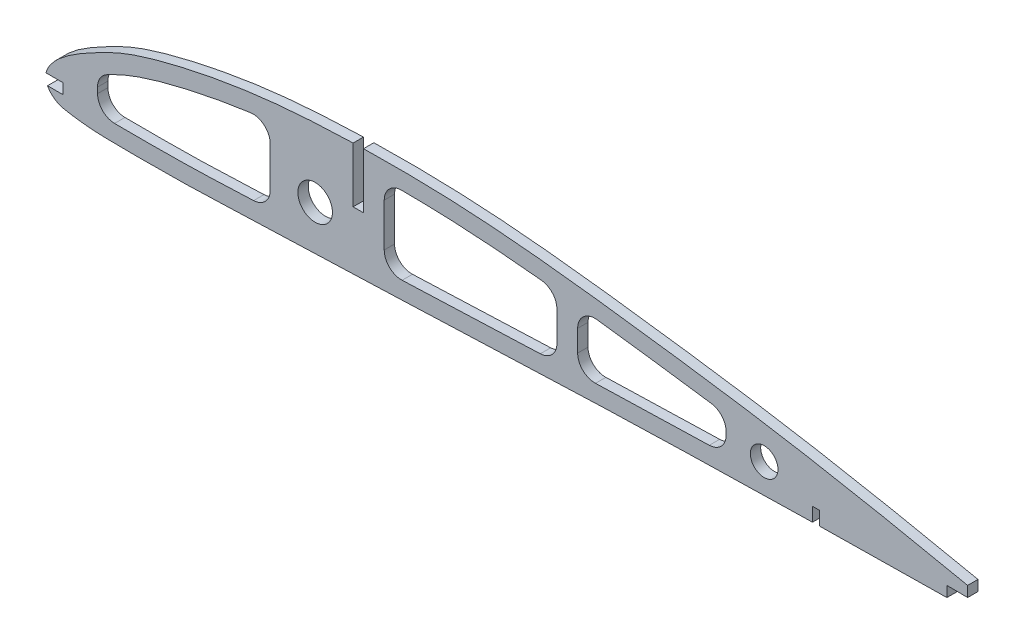
SolidWorks part; units mm, degrees
material "轻木"
ref_plane "前视基准面" through (0, 0, 0) normal (0, 0, 1) x (1, 0, 0)
ref_plane "上视基准面" through (0, 0, 0) normal (0, 1, 0) x (1, 0, 0)
ref_plane "右视基准面" through (0, 0, 0) normal (1, 0, 0) x (0, 0, -1)
other "Configuration Table"
curve "曲线1"
  spline degree 3 poles (300, 0.375, 0) (299.2857, 0.5355, 0) (297.8572, 0.8566, 0) (295.7147, 1.3378, 0) (293.5725, 1.8185, 0) (291.4302, 2.2982, 0) (289.2875, 2.7769, 0) (287.1442, 3.2543, 0) (285.001, 3.7299, 0) (282.8583, 4.2033, 0) (280.7163, 4.6744, 0) (278.5743, 5.1433, 0) (276.432, 5.6099, 0) (274.2889, 6.0741, 0) (272.145, 6.5358, 0) (269.2891, 7.1472, 0) (265.721, 7.9038, 0) (261.4399, 8.8, 0) (257.1573, 9.6847, 0) (252.8725, 10.5577, 0) (248.585, 11.4191, 0) (244.2942, 12.2686, 0) (240.0067, 13.1048, 0) (235.7231, 13.9276, 0) (231.4437, 14.735, 0) (227.1623, 15.5265, 0) (222.8779, 16.3002, 0) (218.5899, 17.0545, 0) (214.2976, 17.7876, 0) (210.0082, 18.4964, 0) (205.7223, 19.1793, 0) (201.441, 19.8388, 0) (197.1575, 20.4787, 0) (192.8717, 21.1016, 0) (188.5834, 21.71, 0) (184.2928, 22.3067, 0) (180.0042, 22.8936, 0) (175.7188, 23.4732, 0) (171.4371, 24.0431, 0) (167.1545, 24.6013, 0) (162.8704, 25.1452, 0) (158.5838, 25.6724, 0) (154.2938, 26.1804, 0) (150.0066, 26.6658, 0) (145.7226, 27.1265, 0) (141.4425, 27.5584, 0) (137.1601, 27.958, 0) (132.875, 28.3213, 0) (128.5869, 28.6439, 0) (124.2953, 28.9218, 0) (120.0053, 29.1506, 0) (115.7177, 29.3264, 0) (111.4337, 29.4514, 0) (107.1488, 29.5275, 0) (102.863, 29.5565, 0) (98.5762, 29.5401, 0) (94.2882, 29.4801, 0) (89.9957, 29.378, 0) (85.6999, 29.236, 0) (81.4026, 29.047, 0) (77.1093, 28.8043, 0) (72.8211, 28.5008, 0) (68.5389, 28.1296, 0) (64.264, 27.6835, 0) (60.7007, 27.2426, 0) (57.8461, 26.8442, 0) (55.696, 26.5216, 0) (53.5496, 26.1773, 0) (51.4067, 25.8115, 0) (49.2673, 25.4247, 0) (47.1314, 25.0171, 0) (44.9882, 24.5868, 0) (42.838, 24.1341, 0) (40.6818, 23.6568, 0) (38.5315, 23.1552, 0) (36.3875, 22.6273, 0) (34.2503, 22.0712, 0) (32.1202, 21.4847, 0) (30.3423, 20.9664, 0) (28.9132, 20.5311, 0) (27.8303, 20.1897, 0) (26.7518, 19.8362, 0) (25.6784, 19.4687, 0) (24.6112, 19.0858, 0) (23.551, 18.6856, 0) (22.4821, 18.2598, 0) (21.4059, 17.8057, 0) (20.3222, 17.3242, 0) (19.2465, 16.8243, 0) (18.1774, 16.3076, 0) (17.1139, 15.7762, 0) (16.0546, 15.2317, 0) (14.9819, 14.6674, 0) (13.8954, 14.0851, 0) (12.7977, 13.4827, 0) (11.7087, 12.8677, 0) (10.6313, 12.2387, 0) (9.5687, 11.5942, 0) (8.5237, 10.9329, 0) (7.6518, 10.3543, 0) (6.9458, 9.8665, 0) (6.3985, 9.4746, 0) (5.8573, 9.0705, 0) (5.3218, 8.651, 0) (4.7913, 8.2128, 0) (4.2653, 7.7527, 0) (3.6165, 7.1497, 0) (2.8604, 6.3846, 0) (2.0362, 5.4343, 0) (1.2959, 4.4252, 0) (0.6772, 3.3675, 0) (0.2189, 2.2697, 0) (-0.0383, 1.1392, 0) (-0.0456, 0.0749, 0) (0.1619, -0.885, 0) (0.4986, -1.7375, 0) (0.9635, -2.5517, 0) (1.5376, -3.3119, 0) (2.2026, -4.0019, 0) (2.94, -4.6051, 0) (3.6355, -5.044, 0) (4.2555, -5.3464, 0) (4.779, -5.5548, 0) (5.3118, -5.728, 0) (5.8521, -5.8723, 0) (6.398, -5.9938, 0) (6.9478, -6.0987, 0) (7.671, -6.2224, 0) (8.5669, -6.3647, 0) (9.636, -6.5177, 0) (10.7063, -6.6545, 0) (11.7778, -6.7754, 0) (12.8506, -6.8809, 0) (13.9246, -6.9713, 0) (14.9978, -7.047, 0) (16.0697, -7.1082, 0) (17.1403, -7.1566, 0) (18.2115, -7.1941, 0) (19.2831, -7.2222, 0) (20.3552, -7.2427, 0) (21.4275, -7.2573, 0) (22.4998, -7.2676, 0) (23.5718, -7.2752, 0) (24.6434, -7.2803, 0) (25.7147, -7.2832, 0) (26.7859, -7.2843, 0) (27.8572, -7.2839, 0) (28.9285, -7.2822, 0) (30.3573, -7.2788, 0) (32.1433, -7.2727, 0) (34.2864, -7.2613, 0) (36.4292, -7.2444, 0) (38.5718, -7.2208, 0) (40.7144, -7.1891, 0) (42.8572, -7.148, 0) (45.0005, -7.0962, 0) (47.1439, -7.0325, 0) (49.2871, -6.9587, 0) (51.4297, -6.8772, 0) (53.572, -6.7902, 0) (55.7143, -6.6999, 0) (57.857, -6.6086, 0) (60.7142, -6.4884, 0) (64.2858, -6.3465, 0) (68.5714, -6.1868, 0) (72.8565, -6.0353, 0) (77.1416, -5.8893, 0) (81.427, -5.7463, 0) (85.7132, -5.6038, 0) (90.0001, -5.4593, 0) (94.287, -5.3101, 0) (98.5731, -5.1566, 0) (102.8583, -4.9992, 0) (107.1431, -4.8383, 0) (111.4281, -4.6742, 0) (115.7138, -4.5074, 0) (120.0001, -4.3383, 0) (124.2865, -4.1673, 0) (128.5722, -3.9953, 0) (132.8572, -3.8233, 0) (137.142, -3.6525, 0) (141.4271, -3.4838, 0) (145.7131, -3.3181, 0) (149.9996, -3.1567, 0) (154.286, -3.0004, 0) (158.5714, -2.8495, 0) (162.8564, -2.7043, 0) (167.1412, -2.5651, 0) (171.4266, -2.4321, 0) (175.7128, -2.3056, 0) (179.9996, -2.1858, 0) (184.2862, -2.0731, 0) (188.5719, -1.9664, 0) (192.857, -1.8646, 0) (197.1419, -1.7668, 0) (201.4272, -1.6719, 0) (205.7132, -1.5788, 0) (209.9999, -1.4865, 0) (214.2864, -1.3941, 0) (218.5722, -1.3027, 0) (222.8572, -1.2136, 0) (227.142, -1.128, 0) (231.4272, -1.0471, 0) (235.7132, -0.9723, 0) (239.9998, -0.9046, 0) (244.2864, -0.8454, 0) (248.5722, -0.7928, 0) (252.8573, -0.7451, 0) (257.1422, -0.7003, 0) (261.4274, -0.6568, 0) (265.7134, -0.6127, 0) (269.2855, -0.574, 0) (272.1433, -0.5408, 0) (274.2862, -0.5157, 0) (276.4287, -0.4908, 0) (278.5712, -0.4671, 0) (280.7137, -0.4452, 0) (282.8567, -0.4258, 0) (285, -0.4096, 0) (287.1432, -0.3973, 0) (289.2862, -0.3884, 0) (291.4287, -0.3824, 0) (293.5711, -0.3786, 0) (295.7137, -0.3765, 0) (297.8567, -0.3754, 0) (299.2855, -0.3751, 0) (300, -0.375, 0) knots 0 0 0 0 0.003574 0.007146 0.010718 0.01429 0.017862 0.021434 0.025008 0.028577 0.032145 0.035713 0.03928 0.042847 0.046415 0.049985 0.057103 0.064219 0.071333 0.078448 0.085563 0.092679 0.099797 0.106885 0.11397 0.121053 0.128137 0.13522 0.142305 0.149391 0.15644 0.163488 0.170534 0.17758 0.184627 0.191675 0.198725 0.205755 0.212782 0.219809 0.226834 0.233861 0.240889 0.24792 0.254921 0.26192 0.268917 0.275914 0.28291 0.289907 0.296905 0.303879 0.310852 0.317824 0.324796 0.331771 0.338748 0.345728 0.352728 0.359727 0.366723 0.373717 0.380709 0.387701 0.394695 0.398233 0.40177 0.405307 0.408843 0.41238 0.415918 0.419457 0.42305 0.426643 0.430235 0.433828 0.43742 0.441014 0.444611 0.446459 0.448306 0.450153 0.451999 0.453844 0.455687 0.45753 0.459459 0.461388 0.463318 0.465249 0.467183 0.469121 0.471062 0.4731 0.475138 0.477173 0.479204 0.481227 0.483239 0.48524 0.486334 0.487428 0.488525 0.48963 0.490748 0.491883 0.493041 0.495071 0.497131 0.499176 0.501171 0.503098 0.50496 0.506796 0.508242 0.509728 0.511253 0.512804 0.514366 0.515919 0.517444 0.518368 0.519283 0.520192 0.521101 0.522011 0.522922 0.523833 0.525592 0.527349 0.529104 0.530859 0.532612 0.534366 0.53612 0.537863 0.539607 0.54135 0.543094 0.544839 0.546584 0.548329 0.550073 0.551817 0.55356 0.555302 0.557045 0.558788 0.560532 0.564019 0.567506 0.570992 0.574478 0.577965 0.581452 0.584939 0.588429 0.591918 0.595406 0.598895 0.602383 0.605872 0.609363 0.616342 0.623319 0.630295 0.637271 0.644247 0.651224 0.658203 0.665183 0.672161 0.679137 0.686114 0.69309 0.700068 0.707048 0.714028 0.721006 0.727983 0.73496 0.741937 0.748915 0.755896 0.762874 0.769851 0.776826 0.783801 0.790777 0.797753 0.804732 0.811709 0.818683 0.825657 0.83263 0.839604 0.846578 0.853555 0.860532 0.867506 0.874479 0.881452 0.888424 0.895399 0.902375 0.90935 0.916324 0.923296 0.930267 0.937239 0.944213 0.951188 0.954676 0.958163 0.961649 0.965135 0.96862 0.972107 0.975595 0.979082 0.982569 0.986054 0.98954 0.993026 0.996512 1 1 1 1
curve "曲线2"
  spline degree 3 poles (299.6892, 0.0825, 0) (300.1498, -0.0478, 0) (299.7114, 0.1074, 0) (299.5104, 0.1872, 0) (299.2477, 0.2871, 0) (298.8504, 0.4413, 0) (298.294, 0.6613, 0) (297.5919, 0.9463, 0) (296.8903, 1.2362, 0) (296.0644, 1.581, 0) (295.1136, 1.9799, 0) (294.0373, 2.431, 0) (292.9597, 2.8788, 0) (291.7683, 3.3665, 0) (290.4608, 3.8877, 0) (289.0365, 4.4399, 0) (287.6073, 4.9796, 0) (286.0635, 5.5484, 0) (284.4048, 6.1444, 0) (282.6311, 6.7664, 0) (280.8534, 7.377, 0) (278.9651, 8.0149, 0) (276.9667, 8.6805, 0) (274.8582, 9.373, 0) (272.7471, 10.0574, 0) (270.5382, 10.7652, 0) (268.2318, 11.4959, 0) (265.8278, 12.2485, 0) (263.4214, 12.9932, 0) (260.9293, 13.7558, 0) (258.3517, 14.5354, 0) (255.6885, 15.3308, 0) (253.0225, 16.1168, 0) (250.2835, 16.9138, 0) (247.4714, 17.7205, 0) (244.5864, 18.536, 0) (241.6982, 19.3402, 0) (238.749, 20.1489, 0) (235.7391, 20.9612, 0) (232.6684, 21.7757, 0) (229.594, 22.5763, 0) (226.4711, 23.374, 0) (223.2997, 24.1675, 0) (220.08, 24.9553, 0) (216.8561, 25.726, 0) (213.5945, 26.4871, 0) (210.2953, 27.2373, 0) (206.9588, 27.975, 0) (203.6178, 28.6919, 0) (200.2497, 29.3918, 0) (196.8549, 30.0732, 0) (193.4336, 30.7349, 0) (190.0077, 31.3718, 0) (186.5618, 31.9862, 0) (183.0963, 32.577, 0) (179.6117, 33.1436, 0) (176.1229, 33.6833, 0) (172.6234, 34.197, 0) (169.1136, 34.6844, 0) (165.5943, 35.1447, 0) (162.0713, 35.5767, 0) (158.5465, 35.9798, 0) (155.0205, 36.3535, 0) (151.4939, 36.6979, 0) (147.9646, 37.0129, 0) (144.4431, 37.2978, 0) (140.9302, 37.5529, 0) (137.4264, 37.7777, 0) (133.9208, 37.9727, 0) (130.4332, 38.1365, 0) (126.9642, 38.269, 0) (123.5147, 38.3706, 0) (120.0643, 38.4412, 0) (116.6408, 38.4803, 0) (113.2449, 38.4881, 0) (109.8772, 38.4649, 0) (106.5099, 38.4098, 0) (103.1795, 38.3231, 0) (99.8867, 38.2053, 0) (96.6323, 38.0567, 0) (93.3796, 37.8749, 0) (90.1728, 37.6618, 0) (87.0127, 37.4182, 0) (83.9, 37.1447, 0) (80.7905, 36.8368, 0) (77.7347, 36.4989, 0) (74.7332, 36.1323, 0) (71.7867, 35.7377, 0) (68.8452, 35.3075, 0) (65.9638, 34.8492, 0) (63.1431, 34.3642, 0) (60.3838, 33.8535, 0) (57.6314, 33.3063, 0) (54.9457, 32.7337, 0) (52.327, 32.1376, 0) (49.7758, 31.5197, 0) (47.2337, 30.8655, 0) (44.763, 30.1905, 0) (42.364, 29.4973, 0) (40.0371, 28.7872, 0) (37.7217, 28.0406, 0) (35.4836, 27.2778, 0) (33.323, 26.5013, 0) (31.2399, 25.7132, 0) (29.1709, 24.8888, 0) (27.1829, 24.0541, 0) (25.2756, 23.212, 0) (23.4491, 22.3647, 0) (21.6401, 21.481, 0) (19.9159, 20.5922, 0) (18.2759, 19.7016, 0) (16.7198, 18.8121, 0) (15.1846, 17.8866, 0) (13.7354, 16.9627, 0) (12.3708, 16.045, 0) (11.0909, 15.1361, 0) (9.8373, 14.192, 0) (8.6721, 13.2572, 0) (7.5935, 12.336, 0) (6.5993, 11.4319, 0) (5.6356, 10.4933, 0) (4.7571, 9.5716, 0) (3.961, 8.6731, 0) (3.2484, 7.802, 0) (2.5791, 6.9017, 0) (2.0018, 6.0303, 0) (1.5119, 5.1928, 0) (1.098, 4.3932, 0) (0.723, 3.565, 0) (0.4148, 2.7772, 0) (0.1635, 2.0409, 0) (-0.0076, 1.362, 0) (-0.0857, 0.6761, 0) (-0.0312, 0.0318, 0) (0.1575, -0.5446, 0) (0.4284, -1.0495, 0) (0.7766, -1.5095, 0) (1.2499, -1.9767, 0) (1.8739, -2.4002, 0) (2.6419, -2.7457, 0) (3.4475, -3.0028, 0) (4.3968, -3.243, 0) (5.4726, -3.4987, 0) (6.6732, -3.7581, 0) (7.8724, -3.9885, 0) (9.2039, -4.2095, 0) (10.6736, -4.4054, 0) (12.2821, -4.571, 0) (13.8972, -4.6995, 0) (15.6445, -4.8094, 0) (17.5211, -4.9053, 0) (19.5261, -4.9826, 0) (21.5305, -5.0368, 0) (23.661, -5.0721, 0) (25.9181, -5.0854, 0) (28.3014, -5.0749, 0) (30.6852, -5.0437, 0) (33.1885, -4.993, 0) (35.8107, -4.9237, 0) (38.5514, -4.8343, 0) (41.2914, -4.7299, 0) (44.1429, -4.6075, 0) (47.1057, -4.467, 0) (50.1792, -4.3077, 0) (53.2522, -4.1367, 0) (56.4269, -3.9498, 0) (59.7026, -3.7473, 0) (63.0791, -3.5293, 0) (66.4551, -3.3033, 0) (69.9209, -3.0645, 0) (73.4761, -2.8134, 0) (77.1202, -2.5502, 0) (80.764, -2.2824, 0) (84.4846, -2.0051, 0) (88.2815, -1.7191, 0) (92.1543, -1.4245, 0) (96.027, -1.128, 0) (99.9621, -0.8252, 0) (103.9592, -0.5167, 0) (108.0179, -0.2032, 0) (112.0767, 0.1098, 0) (116.1823, 0.4251, 0) (120.3344, 0.742, 0) (124.5324, 1.0596, 0) (128.7308, 1.3739, 0) (132.9595, 1.6861, 0) (137.2181, 1.9957, 0) (141.506, 2.3018, 0) (145.7945, 2.6016, 0) (150.096, 2.8954, 0) (154.41, 3.1825, 0) (158.7362, 3.4618, 0) (163.063, 3.7316, 0) (167.3848, 3.9907, 0) (171.7011, 4.2382, 0) (176.0115, 4.4733, 0) (180.3226, 4.6957, 0) (184.6083, 4.9033, 0) (188.8679, 5.0957, 0) (193.1011, 5.2721, 0) (197.335, 5.4325, 0) (201.5222, 5.5742, 0) (205.6623, 5.6969, 0) (209.7546, 5.8004, 0) (213.8473, 5.8854, 0) (217.8716, 5.9498, 0) (221.8268, 5.9942, 0) (225.7124, 6.0188, 0) (229.598, 6.0233, 0) (233.3935, 6.0071, 0) (237.0983, 5.971, 0) (240.7119, 5.9157, 0) (244.325, 5.8393, 0) (247.8275, 5.7436, 0) (251.2186, 5.6301, 0) (254.498, 5.5, 0) (257.7765, 5.3484, 0) (260.9253, 5.1809, 0) (263.9441, 4.9996, 0) (266.8324, 4.8058, 0) (269.7191, 4.5899, 0) (272.4587, 4.362, 0) (275.0509, 4.1249, 0) (277.4951, 3.8799, 0) (279.9368, 3.6105, 0) (282.2113, 3.3338, 0) (284.3185, 3.0537, 0) (286.2585, 2.7745, 0) (288.195, 2.4723, 0) (289.9467, 2.1761, 0) (291.5141, 1.8919, 0) (292.8979, 1.6262, 0) (294.2788, 1.3456, 0) (295.4709, 1.0894, 0) (296.4751, 0.8638, 0) (297.2928, 0.6738, 0) (298.1076, 0.4784, 0) (298.7442, 0.3204, 0) (299.1896, 0.208, 0) (299.4728, 0.1348, 0) (299.6892, 0.0825, 0) (300.1498, -0.0478, 0) (299.7114, 0.1074, 0) knots -0.001345 -0.000897 -0.000449 0 0.000432 0.000863 0.001295 0.001726 0.002951 0.004176 0.0054 0.006625 0.008509 0.010392 0.012274 0.014158 0.016623 0.019088 0.021553 0.024019 0.027053 0.030085 0.033118 0.036152 0.039734 0.043315 0.046896 0.050478 0.054544 0.058608 0.062672 0.066738 0.071224 0.075709 0.080193 0.084679 0.089518 0.094356 0.099193 0.104032 0.10916 0.114286 0.119411 0.124539 0.129889 0.135237 0.140585 0.145936 0.151451 0.156964 0.162478 0.167993 0.173617 0.17924 0.184862 0.190486 0.196184 0.20188 0.207576 0.213274 0.219003 0.22473 0.230457 0.236185 0.241905 0.247622 0.253339 0.259058 0.264725 0.270389 0.276054 0.281721 0.287291 0.29286 0.298428 0.303998 0.309434 0.314867 0.320301 0.325737 0.330995 0.336251 0.341507 0.346766 0.351809 0.356851 0.361892 0.366936 0.371734 0.37653 0.381327 0.386125 0.390654 0.395182 0.399709 0.404238 0.408475 0.41271 0.416945 0.421182 0.425109 0.429034 0.432959 0.436885 0.44048 0.444073 0.447666 0.451261 0.454511 0.457759 0.461007 0.464256 0.467149 0.470041 0.472933 0.475826 0.47836 0.480893 0.483425 0.485956 0.488123 0.490291 0.49246 0.494634 0.496453 0.49827 0.500081 0.501882 0.503328 0.504776 0.506239 0.507727 0.50887 0.510003 0.51111 0.512198 0.513104 0.514027 0.514959 0.515886 0.517235 0.518584 0.51995 0.521324 0.523324 0.525303 0.52727 0.529235 0.531836 0.534446 0.537062 0.539679 0.542921 0.546158 0.549393 0.552628 0.556473 0.560319 0.564166 0.568014 0.57244 0.576864 0.581288 0.585714 0.590681 0.595647 0.600613 0.605581 0.611042 0.616501 0.62196 0.627422 0.633319 0.639214 0.645109 0.651006 0.657275 0.663542 0.669809 0.676078 0.682648 0.689216 0.695784 0.702355 0.70915 0.715943 0.722736 0.729531 0.73647 0.743406 0.750342 0.757281 0.764278 0.771273 0.778268 0.785265 0.792232 0.799197 0.806162 0.81313 0.819969 0.826805 0.833641 0.840479 0.847087 0.853692 0.860297 0.866904 0.873175 0.879445 0.885714 0.891986 0.897819 0.90365 0.909481 0.915314 0.920611 0.925907 0.931202 0.936499 0.941172 0.945842 0.950513 0.955185 0.95915 0.963114 0.967077 0.971042 0.974206 0.977368 0.98053 0.983693 0.985968 0.988241 0.990515 0.992789 0.994144 0.995498 0.996852 0.998206 0.998655 0.999103 0.999551 1 1.000432 1.000863 1.001295 periodic
sketch "草图1" plane through (0, 0, 0) normal (0, 0, 1) x (1, 0, 0)
  line L1 (290, 2.6177) -> (290, -0.3866)
  line L2 (289, 1.8162) -> (289, 0.6101)
  line L3 (0, 0) -> (0, 30) construction
  line L4 (-6, -1.5) -> (6, -1.5)
  line L5 (-6, -1.5) -> (-6, 1.5)
  line L6 (-6, 1.5) -> (6, 1.5)
  line L7 (6, -1.5) -> (6, 1.5)
  line L8 (-6, -1.5) -> (6, 1.5) construction
  line L9 (-6, 1.5) -> (6, -1.5) construction
  line L10 (-1000, 0) -> (49000, 0) construction
  line L11 (90, 29.3715) -> (93, 29.3715)
  line L12 (90, 29.3715) -> (90, 12.3715)
  line L13 (90, 12.3715) -> (93, 12.3715)
  line L14 (93, 29.3715) -> (93, 12.3715)
  line L16 (223, -1.2113) -> (225, -1.2113)
  line L17 (223, -1.2113) -> (223, 3.7887)
  line L18 (223, 3.7887) -> (225, 3.7887)
  line L19 (225, -1.2113) -> (225, 3.7887)
  circle A0 centre (79, 8) radius 5
  circle A1 centre (209, 8) radius 4
  spline S0 degree 3 poles (1772.1833, 2527.0993) (871.6721, -135.2205) (584.8189, -63.6019) (295.7147, 1.3378) (293.5725, 1.8185) (291.4302, 2.2982) (289.2875, 2.7769) (287.1442, 3.2543) (285.001, 3.7299) (282.8583, 4.2033) (280.7163, 4.6744) (278.5743, 5.1433) (276.432, 5.6099) (274.2889, 6.0741) (272.145, 6.5358) (269.2891, 7.1472) (265.721, 7.9038) (261.4399, 8.8) (257.1573, 9.6847) (252.8725, 10.5577) (248.585, 11.4191) (244.2942, 12.2686) (240.0067, 13.1048) (234.2978, 14.2013) (228.5907, 15.2685) (222.8779, 16.3002) (218.5899, 17.0545) (214.2976, 17.7876) (210.0082, 18.4964) (205.7223, 19.1793) (201.441, 19.8388) (197.1575, 20.4787) (192.8717, 21.1016) (188.5834, 21.71) (184.2928, 22.3067) (180.0042, 22.8936) (175.7188, 23.4732) (171.4371, 24.0431) (167.1545, 24.6013) (162.8704, 25.1452) (158.5838, 25.6724) (154.2938, 26.1804) (150.0066, 26.6658) (145.7226, 27.1265) (141.4425, 27.5584) (137.1601, 27.958) (132.875, 28.3213) (128.5869, 28.6439) (124.2953, 28.9218) (120.0053, 29.1506) (115.7177, 29.3264) (111.4337, 29.4514) (107.1488, 29.5275) (102.863, 29.5565) (98.5762, 29.5401) (94.2882, 29.4801) (89.9957, 29.378) (85.6999, 29.236) (81.4026, 29.047) (77.1093, 28.8043) (72.8211, 28.5008) (68.5389, 28.1296) (64.264, 27.6835) (60.7007, 27.2426) (57.1284, 26.744) (53.5478, 26.188) (49.9791, 25.5605) (47.1314, 25.0171) (44.9882, 24.5868) (42.838, 24.1341) (40.6818, 23.6568) (38.5315, 23.1552) (36.3875, 22.6273) (34.2503, 22.0712) (32.1202, 21.4847) (30.3423, 20.9664) (28.9132, 20.5311) (27.8303, 20.1897) (26.7518, 19.8362) (25.6784, 19.4687) (24.6112, 19.0858) (23.551, 18.6856) (22.4821, 18.2598) (21.4059, 17.8057) (20.3222, 17.3242) (19.2465, 16.8243) (18.1774, 16.3076) (17.1139, 15.7762) (16.0546, 15.2317) (14.9819, 14.6674) (13.8954, 14.0851) (12.7977, 13.4827) (11.7087, 12.8677) (10.6313, 12.2387) (9.5687, 11.5942) (8.5237, 10.9329) (7.6518, 10.3543) (6.9458, 9.8665) (6.3985, 9.4746) (5.8573, 9.0705) (5.3218, 8.651) (4.7913, 8.2128) (4.2653, 7.7527) (3.6165, 7.1497) (2.8604, 6.3846) (2.0362, 5.4343) (1.2959, 4.4252) (0.6772, 3.3675) (0.2189, 2.2697) (-0.0383, 1.1392) (-0.0456, 0.0749) (0.1619, -0.885) (0.4986, -1.7375) (0.9635, -2.5517) (1.5376, -3.3119) (2.2026, -4.0019) (2.94, -4.6051) (3.6355, -5.044) (4.2555, -5.3464) (4.779, -5.5548) (5.3118, -5.728) (5.8521, -5.8723) (6.398, -5.9938) (6.9478, -6.0987) (7.671, -6.2224) (8.5669, -6.3647) (9.9918, -6.5686) (11.4199, -6.7402) (12.8506, -6.8809) (13.9246, -6.9713) (14.9978, -7.047) (16.0697, -7.1082) (17.1403, -7.1566) (18.2115, -7.1941) (19.2831, -7.2222) (20.3552, -7.2427) (21.4275, -7.2573) (22.4998, -7.2676) (23.5718, -7.2752) (24.6434, -7.2803) (25.7147, -7.2832) (27.143, -7.2847) (28.5715, -7.283) (30.3573, -7.2788) (32.1433, -7.2727) (34.2864, -7.2613) (36.4292, -7.2444) (38.5718, -7.2208) (40.7144, -7.1891) (42.8572, -7.148) (45.0005, -7.0962) (47.1439, -7.0325) (49.2871, -6.9587) (51.4297, -6.8772) (54.2862, -6.7612) (57.1429, -6.6386) (60.7142, -6.4884) (64.2858, -6.3465) (69.9995, -6.1336) (75.7132, -5.9369) (81.427, -5.7463) (85.7132, -5.6038) (90.0001, -5.4593) (94.287, -5.3101) (98.5731, -5.1566) (102.8583, -4.9992) (108.5717, -4.7846) (114.2856, -4.5638) (120.0001, -4.3383) (124.2865, -4.1673) (128.5722, -3.9953) (132.8572, -3.8233) (137.142, -3.6525) (141.4271, -3.4838) (145.7131, -3.3181) (149.9996, -3.1567) (154.286, -3.0004) (158.5714, -2.8495) (164.2846, -2.656) (171.4272, -2.4288) (179.9991, -2.1823) (187.1429, -2.0003) (192.857, -1.8646) (197.1419, -1.7668) (201.4272, -1.6719) (205.7132, -1.5788) (209.9999, -1.4865) (214.2864, -1.3941) (218.5722, -1.3027) (222.8572, -1.2136) (227.142, -1.128) (231.4272, -1.0471) (235.7132, -0.9723) (239.9998, -0.9046) (244.2864, -0.8454) (248.5722, -0.7928) (252.8573, -0.7451) (258.5708, -0.6854) (264.285, -0.6282) (269.2855, -0.574) (272.1433, -0.5408) (274.2862, -0.5157) (276.4287, -0.4908) (278.5712, -0.4671) (280.7137, -0.4452) (282.8567, -0.4258) (285, -0.4096) (287.1432, -0.3973) (289.2862, -0.3884) (291.4287, -0.3824) (293.5711, -0.3786) (295.7137, -0.3765) (521.6922, -0.2702) (746.959, -9.4705) (970.7683, 2878.2814) knots -1.435568 -1.435568 -1.435568 -1.435568 0.003574 0.007146 0.010718 0.01429 0.017862 0.021434 0.025008 0.028577 0.032145 0.035713 0.03928 0.042847 0.046415 0.049985 0.057103 0.064219 0.071333 0.078448 0.085563 0.092679 0.099797 0.106885 0.121053 0.128137 0.13522 0.142305 0.149391 0.15644 0.163488 0.170534 0.17758 0.184627 0.191675 0.198725 0.205755 0.212782 0.219809 0.226834 0.233861 0.240889 0.24792 0.254921 0.26192 0.268917 0.275914 0.28291 0.289907 0.296905 0.303879 0.310852 0.317824 0.324796 0.331771 0.338748 0.345728 0.352728 0.359727 0.366723 0.373717 0.380709 0.387701 0.394695 0.398233 0.405307 0.41238 0.415918 0.419457 0.42305 0.426643 0.430235 0.433828 0.43742 0.441014 0.444611 0.446459 0.448306 0.450153 0.451999 0.453844 0.455687 0.45753 0.459459 0.461388 0.463318 0.465249 0.467183 0.469121 0.471062 0.4731 0.475138 0.477173 0.479204 0.481227 0.483239 0.48524 0.486334 0.487428 0.488525 0.48963 0.490748 0.491883 0.493041 0.495071 0.497131 0.499176 0.501171 0.503098 0.50496 0.506796 0.508242 0.509728 0.511253 0.512804 0.514366 0.515919 0.517444 0.518368 0.519283 0.520192 0.521101 0.522011 0.522922 0.523833 0.525592 0.527349 0.530859 0.532612 0.534366 0.53612 0.537863 0.539607 0.54135 0.543094 0.544839 0.546584 0.548329 0.550073 0.551817 0.55356 0.555302 0.558788 0.560532 0.564019 0.567506 0.570992 0.574478 0.577965 0.581452 0.584939 0.588429 0.591918 0.595406 0.598895 0.605872 0.609363 0.616342 0.623319 0.637271 0.644247 0.651224 0.658203 0.665183 0.672161 0.679137 0.686114 0.700068 0.707048 0.714028 0.721006 0.727983 0.73496 0.741937 0.748915 0.755896 0.762874 0.769851 0.776826 0.790777 0.804732 0.818683 0.825657 0.83263 0.839604 0.846578 0.853555 0.860532 0.867506 0.874479 0.881452 0.888424 0.895399 0.902375 0.90935 0.916324 0.923296 0.930267 0.944213 0.951188 0.954676 0.958163 0.961649 0.965135 0.96862 0.972107 0.975595 0.979082 0.982569 0.986054 0.98954 0.993026 0.996512 2.092547 2.092547 2.092547 2.092547 only from (300, 0.375) to (300, -0.375) construction
  spline S1 degree 3 poles (290, 2.6177) (289.0482, 2.8302) (287.3817, 3.2016) (285.001, 3.7299) (282.8583, 4.2033) (280.7163, 4.6744) (278.5743, 5.1433) (276.432, 5.6099) (274.2889, 6.0741) (272.145, 6.5358) (269.2891, 7.1472) (265.721, 7.9038) (261.4399, 8.8) (257.1573, 9.6847) (252.8725, 10.5577) (248.585, 11.4191) (244.2942, 12.2686) (240.0067, 13.1048) (234.2978, 14.2013) (228.5907, 15.2685) (222.8779, 16.3002) (218.5899, 17.0545) (214.2976, 17.7876) (210.0082, 18.4964) (205.7223, 19.1793) (201.441, 19.8388) (197.1575, 20.4787) (192.8717, 21.1016) (188.5834, 21.71) (184.2928, 22.3067) (180.0042, 22.8936) (175.7188, 23.4732) (171.4371, 24.0431) (167.1545, 24.6013) (162.8704, 25.1452) (158.5838, 25.6724) (154.2938, 26.1804) (150.0066, 26.6658) (145.7226, 27.1265) (141.4425, 27.5584) (137.1601, 27.958) (132.875, 28.3213) (128.5869, 28.6439) (124.2953, 28.9218) (120.0053, 29.1506) (115.7177, 29.3264) (111.4337, 29.4514) (107.1488, 29.5275) (102.863, 29.5565) (98.5762, 29.5401) (94.2882, 29.4801) (89.9957, 29.378) (85.6999, 29.236) (81.4026, 29.047) (77.1093, 28.8043) (72.8211, 28.5008) (68.5389, 28.1296) (64.264, 27.6835) (60.7007, 27.2426) (57.1284, 26.744) (53.5478, 26.188) (49.9791, 25.5605) (47.1314, 25.0171) (44.9882, 24.5868) (42.838, 24.1341) (40.6818, 23.6568) (38.5315, 23.1552) (36.3875, 22.6273) (34.2503, 22.0712) (32.1202, 21.4847) (30.3423, 20.9664) (28.9132, 20.5311) (27.8303, 20.1897) (26.7518, 19.8362) (25.6784, 19.4687) (24.6112, 19.0858) (23.551, 18.6856) (22.4821, 18.2598) (21.4059, 17.8057) (20.3222, 17.3242) (19.2465, 16.8243) (18.1774, 16.3076) (17.1139, 15.7762) (16.0546, 15.2317) (14.9819, 14.6674) (13.8954, 14.0851) (12.7977, 13.4827) (11.7087, 12.8677) (10.6313, 12.2387) (9.5687, 11.5942) (8.5237, 10.9329) (7.6518, 10.3543) (6.9458, 9.8665) (6.3985, 9.4746) (5.8573, 9.0705) (5.3218, 8.651) (4.7913, 8.2128) (4.2653, 7.7527) (3.6165, 7.1497) (2.8604, 6.3846) (2.0362, 5.4343) (1.2959, 4.4252) (0.6772, 3.3675) (0.2189, 2.2697) (-0.0383, 1.1392) (-0.0456, 0.0749) (0.1619, -0.885) (0.4986, -1.7375) (0.9635, -2.5517) (1.5376, -3.3119) (2.2026, -4.0019) (2.94, -4.6051) (3.6355, -5.044) (4.2555, -5.3464) (4.779, -5.5548) (5.3118, -5.728) (5.8521, -5.8723) (6.398, -5.9938) (6.9478, -6.0987) (7.671, -6.2224) (8.5669, -6.3647) (9.9918, -6.5686) (11.4199, -6.7402) (12.8506, -6.8809) (13.9246, -6.9713) (14.9978, -7.047) (16.0697, -7.1082) (17.1403, -7.1566) (18.2115, -7.1941) (19.2831, -7.2222) (20.3552, -7.2427) (21.4275, -7.2573) (22.4998, -7.2676) (23.5718, -7.2752) (24.6434, -7.2803) (25.7147, -7.2832) (27.143, -7.2847) (28.5715, -7.283) (30.3573, -7.2788) (32.1433, -7.2727) (34.2864, -7.2613) (36.4292, -7.2444) (38.5718, -7.2208) (40.7144, -7.1891) (42.8572, -7.148) (45.0005, -7.0962) (47.1439, -7.0325) (49.2871, -6.9587) (51.4297, -6.8772) (54.2862, -6.7612) (57.1429, -6.6386) (60.7142, -6.4884) (64.2858, -6.3465) (69.9995, -6.1336) (75.7132, -5.9369) (81.427, -5.7463) (85.7132, -5.6038) (90.0001, -5.4593) (94.287, -5.3101) (98.5731, -5.1566) (102.8583, -4.9992) (108.5717, -4.7846) (114.2856, -4.5638) (120.0001, -4.3383) (124.2865, -4.1673) (128.5722, -3.9953) (132.8572, -3.8233) (137.142, -3.6525) (141.4271, -3.4838) (145.7131, -3.3181) (149.9996, -3.1567) (154.286, -3.0004) (158.5714, -2.8495) (164.2846, -2.656) (171.4272, -2.4288) (179.9991, -2.1823) (187.1429, -2.0003) (192.857, -1.8646) (197.1419, -1.7668) (201.4272, -1.6719) (205.7132, -1.5788) (209.9999, -1.4865) (214.2864, -1.3941) (218.5722, -1.3027) (222.8572, -1.2136) (227.142, -1.128) (231.4272, -1.0471) (235.7132, -0.9723) (239.9998, -0.9046) (244.2864, -0.8454) (248.5722, -0.7928) (252.8573, -0.7451) (258.5708, -0.6854) (264.285, -0.6282) (269.2855, -0.574) (272.1433, -0.5408) (274.2862, -0.5157) (276.4287, -0.4908) (278.5712, -0.4671) (280.7137, -0.4452) (282.8567, -0.4258) (285, -0.4096) (287.1432, -0.3973) (288.8099, -0.3904) (289.7621, -0.3873) (290, -0.3866) knots 0.016674 0.016674 0.016674 0.016674 0.021434 0.025008 0.028577 0.032145 0.035713 0.03928 0.042847 0.046415 0.049985 0.057103 0.064219 0.071333 0.078448 0.085563 0.092679 0.099797 0.106885 0.121053 0.128137 0.13522 0.142305 0.149391 0.15644 0.163488 0.170534 0.17758 0.184627 0.191675 0.198725 0.205755 0.212782 0.219809 0.226834 0.233861 0.240889 0.24792 0.254921 0.26192 0.268917 0.275914 0.28291 0.289907 0.296905 0.303879 0.310852 0.317824 0.324796 0.331771 0.338748 0.345728 0.352728 0.359727 0.366723 0.373717 0.380709 0.387701 0.394695 0.398233 0.405307 0.41238 0.415918 0.419457 0.42305 0.426643 0.430235 0.433828 0.43742 0.441014 0.444611 0.446459 0.448306 0.450153 0.451999 0.453844 0.455687 0.45753 0.459459 0.461388 0.463318 0.465249 0.467183 0.469121 0.471062 0.4731 0.475138 0.477173 0.479204 0.481227 0.483239 0.48524 0.486334 0.487428 0.488525 0.48963 0.490748 0.491883 0.493041 0.495071 0.497131 0.499176 0.501171 0.503098 0.50496 0.506796 0.508242 0.509728 0.511253 0.512804 0.514366 0.515919 0.517444 0.518368 0.519283 0.520192 0.521101 0.522011 0.522922 0.523833 0.525592 0.527349 0.530859 0.532612 0.534366 0.53612 0.537863 0.539607 0.54135 0.543094 0.544839 0.546584 0.548329 0.550073 0.551817 0.55356 0.555302 0.558788 0.560532 0.564019 0.567506 0.570992 0.574478 0.577965 0.581452 0.584939 0.588429 0.591918 0.595406 0.598895 0.605872 0.609363 0.616342 0.623319 0.637271 0.644247 0.651224 0.658203 0.665183 0.672161 0.679137 0.686114 0.700068 0.707048 0.714028 0.721006 0.727983 0.73496 0.741937 0.748915 0.755896 0.762874 0.769851 0.776826 0.790777 0.804732 0.818683 0.825657 0.83263 0.839604 0.846578 0.853555 0.860532 0.867506 0.874479 0.881452 0.888424 0.895399 0.902375 0.90935 0.916324 0.923296 0.930267 0.944213 0.951188 0.954676 0.958163 0.961649 0.965135 0.96862 0.972107 0.975595 0.979082 0.982569 0.98373 0.98373 0.98373 0.98373
  spline S2 degree 1 poles (289, 1.8162) (289, 0.6101) knots 0 0 1 1 construction
  spline S3 degree 3 poles (289, 1.8162) (276.9573, 4.5023) (258.8616, 8.3976) (234.6482, 13.1528) (216.4485, 16.4789) (198.1829, 19.3716) (179.8506, 21.9241) (161.5032, 24.3586) (143.1279, 26.4732) (124.7122, 28.0438) (106.2546, 28.676) (87.7718, 28.43) (72.4033, 27.5865) (60.1859, 26.2263) (51.081, 24.7981) (42.0339, 23.0001) (34.582, 21.1749) (28.6974, 19.4456) (24.362, 17.9834) (20.1748, 16.2079) (16.0789, 14.1399) (12.0403, 11.9468) (8.1401, 9.5604) (5.1537, 7.3164) (3.1001, 5.2006) (1.8138, 3.4707) (0.9689, 1.5796) (0.9059, -0.2656) (1.7459, -2.0716) (3.1431, -3.6011) (4.8543, -4.6194) (6.9276, -5.1056) (9.209, -5.4548) (12.22, -5.8429) (16.0201, -6.1427) (20.6095, -6.2611) (25.2315, -6.2869) (31.3974, -6.2803) (39.1073, -6.2407) (48.3368, -6.0221) (57.5799, -5.613) (66.8407, -5.2429) (76.0966, -4.9217) (88.436, -4.516) (103.8531, -3.9731) (122.3546, -3.2481) (140.8578, -2.4955) (159.3685, -1.8041) (177.8842, -1.2225) (196.4034, -0.7749) (214.9166, -0.3802) (233.434, 0.0126) (251.9612, 0.2567) (270.4719, 0.4292) (282.8248, 0.5874) (289, 0.6101) knots 0.017978 0.017978 0.017978 0.017978 0.078237 0.108366 0.138495 0.168624 0.198753 0.228882 0.259011 0.28914 0.319269 0.349398 0.379527 0.394592 0.409656 0.424721 0.439785 0.447318 0.45485 0.462382 0.469915 0.477447 0.484979 0.492511 0.496277 0.500044 0.50381 0.507576 0.511342 0.515108 0.518874 0.52264 0.526407 0.530173 0.537705 0.545237 0.552769 0.560302 0.575366 0.590431 0.605495 0.62056 0.635624 0.650689 0.680818 0.710947 0.741076 0.771205 0.801334 0.831463 0.861593 0.891722 0.921851 0.95198 0.982109 0.982109 0.982109 0.982109
  point P8 (0, 0)
  dimension "D9" = 10
  dimension "D10" = 8
  dimension "D1" = 290
  dimension "D2" = 1
  dimension "D3" = 12
  dimension "D4" = 3
  dimension "D5" = 30
  dimension "D6" = 3
  dimension "D7" = 17
  dimension "D8" = 90
  dimension "D11" = 130
  dimension "D12" = 11
  dimension "D13" = 8
  dimension "D14" = 5
  dimension "D15" = 2
  dimension "D16" = 130
extrude "凸台-拉伸1" add sketch "草图1" along normal blind 3 contours L2 S3 | S1 L1
sketch "草图3" plane through (0, 0, 0) normal (0, 0, 1) x (1, 0, 0)
  line L5 (261.9131, 3.4122) -> (261.9131, 0.3499)
  line L6 (261.9131, 0.3499) -> (296.9131, 0.3499)
  line L10 (16, 5.403) -> (16, 3.7496)
  line L15 (66, 16.1752) -> (66, 4.5297)
  line L16 (99, 18.546) -> (99, 6.0517)
  line L17 (149, 16.2416) -> (149, 7.6232)
  line L18 (155, 14.4146) -> (155, 8.2048)
  line L19 (198, 9.9673) -> (198, 9.1407)
  line L20 (93, 28.4491) -> (93, 12.3715) construction
  line L21 (296.9131, 0.3499) -> (267.9131, 6.4122)
  line L22 (267.9131, 7.4345) -> (267.9131, 6.4122) construction
  line L23 (267.9131, 6.4122) -> (267.9131, 3.3622)
  line L24 (307.9131, 3.3622) -> (267.9131, 3.3622) construction
  line L25 (267.9131, 3.3622) -> (261.9131, 3.4122)
  arc A0 (198, 9.1407) -> (193.1165, 4.142) centre (193, 9.1407) cw
  arc A1 (198, 9.9673) -> (193.7184, 14.9154) centre (193, 9.9673) ccw
  arc A2 (155, 8.2048) -> (160.1704, 3.2078) centre (160, 8.2048) ccw
  arc A3 (155, 14.4146) -> (160.6135, 19.3768) centre (160, 14.4146) cw
  arc A4 (149, 16.2416) -> (144.5132, 21.2152) centre (144, 16.2416) ccw
  arc A5 (149, 7.6232) -> (144.1914, 2.6268) centre (144, 7.6232) cw
  arc A6 (99, 6.0517) -> (104.1864, 1.0552) centre (104, 6.0517) ccw
  arc A7 (99, 18.546) -> (104.0243, 23.5459) centre (104, 18.546) cw
  arc A8 (66, 16.1752) -> (60.3235, 21.1292) centre (61, 16.1752) ccw
  arc A9 (66, 4.5297) -> (61.2015, -0.4662) centre (61, 4.5297) cw
  arc A10 (16, 3.7496) -> (20.9267, -1.2499) centre (21, 3.7496) ccw
  arc A11 (16, 5.403) -> (18.6935, 9.8392) centre (21, 5.403) cw
  spline S0 degree 3 poles (144.5132, 21.2152) (143.6521, 21.3041) (142.7912, 21.3911) (137.8564, 21.8798) (133.7874, 22.2409) (125.6593, 22.8404) (121.6016, 23.0755) (113.0376, 23.4243) (108.5326, 23.524) (104.0243, 23.5459) knots 0.736794 0.736794 0.736794 0.736794 0.75 0.75 0.8125 0.8125 0.875 0.875 0.944193 0.944193 0.944193 0.944193
  spline S1 degree 3 poles (160.1704, 3.2078) (162.3897, 3.2834) (164.6093, 3.3568) (171.5046, 3.5762) (176.182, 3.7134) (184.9459, 3.9468) (189.0321, 4.0469) (193.1165, 4.142) knots 0.720326 0.720326 0.720326 0.720326 0.75 0.75 0.8125 0.8125 0.867134 0.867134 0.867134 0.867134
  spline S2 degree 3 poles (104.1864, 1.0552) (106.3946, 1.1375) (108.6029, 1.2214) (120.1319, 1.6658) (129.4563, 2.0501) (140.5926, 2.488) (142.3918, 2.5579) (144.1914, 2.6268) knots 0.470377 0.470377 0.470377 0.470377 0.5 0.5 0.625 0.625 0.649082 0.649082 0.649082 0.649082
  spline S3 degree 3 poles (2123.5032, -6666.5942) (57.8153, -27.8856) (3.0893, 4.8913) (6.0465, 0.6803) (6.0902, 0.6246) (6.1868, 0.5153) (6.2397, 0.4617) (6.3456, 0.3655) (6.3976, 0.3236) (6.5437, 0.2182) (6.6312, 0.1692) (6.7722, 0.1112) (6.804, 0.099) (6.8878, 0.0698) (6.9381, 0.0536) (7.1139, 0.0015) (7.2645, -0.0375) (7.537, -0.0984) (7.6355, -0.1192) (7.8472, -0.1616) (7.9613, -0.1834) (8.3094, -0.2477) (8.5533, -0.2893) (9.0582, -0.3705) (9.3192, -0.41) (9.8531, -0.4875) (10.1264, -0.5257) (10.9344, -0.635) (11.4671, -0.7017) (12.5267, -0.821) (13.0591, -0.8742) (14.6647, -1.0159) (15.7434, -1.0862) (17.929, -1.1862) (19.0402, -1.2168) (21.2997, -1.2581) (22.4443, -1.2693) (24.7448, -1.282) (25.9034, -1.2838) (29.3811, -1.2835) (31.7096, -1.2772) (36.344, -1.2483) (38.6522, -1.2235) (43.2612, -1.1389) (45.5633, -1.0801) (50.1682, -0.9268) (52.4816, -0.8311) (57.1372, -0.634) (59.4794, -0.5349) (64.1588, -0.348) (66.5002, -0.2589) (73.5178, -0.0049) (78.1885, 0.1484) (87.5159, 0.4597) (92.1745, 0.6196) (101.4932, 0.9531) (106.1515, 1.1269) (120.1319, 1.6658) (129.4563, 2.0501) (148.1311, 2.7844) (157.4781, 3.1298) (171.5046, 3.5762) (176.182, 3.7134) (185.5345, 3.9625) (190.2088, 4.0755) (199.5523, 4.2901) (204.2219, 4.392) (610.7173, 13.1072) (998.0302, 23.4562) (6461.7434, -3116.409) knots -0.312717 -0.312717 -0.312717 -0.312717 0.003906 0.003906 0.007813 0.007813 0.011719 0.011719 0.015625 0.015625 0.023438 0.023438 0.025391 0.025391 0.027344 0.027344 0.03125 0.03125 0.033203 0.033203 0.035156 0.035156 0.039063 0.039063 0.042969 0.042969 0.046875 0.046875 0.054688 0.054688 0.0625 0.0625 0.078125 0.078125 0.09375 0.09375 0.109375 0.109375 0.125 0.125 0.15625 0.15625 0.1875 0.1875 0.21875 0.21875 0.25 0.25 0.28125 0.28125 0.3125 0.3125 0.375 0.375 0.4375 0.4375 0.5 0.5 0.625 0.625 0.75 0.75 0.8125 0.8125 0.875 0.875 0.9375 0.9375 6.317075 6.317075 6.317075 6.317075 only from (5.9323, 0.8564) to (222.8977, 4.7881)
  spline S4 degree 3 poles (225, -0.1703) (227.8116, -0.114) (236.7968, 0.0569) (251.9612, 0.2567) (270.4719, 0.4292) (282.8248, 0.5874) (289, 0.6101) knots 0.877998 0.877998 0.877998 0.877998 0.891722 0.921851 0.95198 0.982109 0.982109 0.982109 0.982109 construction
  spline S5 degree 3 poles (289, 1.8162) (276.9573, 4.5023) (258.8616, 8.3976) (234.6482, 13.1528) (216.4485, 16.4789) (198.1829, 19.3716) (179.8506, 21.9241) (161.5032, 24.3586) (143.1279, 26.4732) (124.7122, 28.0438) (107.9942, 28.6164) (97.4163, 28.5467) (93, 28.4491) knots 0.017978 0.017978 0.017978 0.017978 0.078237 0.108366 0.138495 0.168624 0.198753 0.228882 0.259011 0.28914 0.319269 0.34088 0.34088 0.34088 0.34088 construction
  spline S6 degree 3 poles (20.9267, -1.2499) (21.8097, -1.2628) (22.7004, -1.2707) (24.7448, -1.282) (25.9034, -1.2838) (29.3811, -1.2835) (31.7096, -1.2772) (36.344, -1.2483) (38.6522, -1.2235) (43.2612, -1.1389) (45.5633, -1.0801) (50.1682, -0.9268) (52.4816, -0.8311) (56.9324, -0.6427) (59.0674, -0.5523) (61.2015, -0.4662) knots 0.097229 0.097229 0.097229 0.097229 0.109375 0.109375 0.125 0.125 0.15625 0.15625 0.1875 0.1875 0.21875 0.21875 0.25 0.25 0.278501 0.278501 0.278501 0.278501
  spline S7 degree 3 poles (2473.6517, 4175.1569) (1319.8259, -493.6171) (810.8225, -112.9481) (255.6753, 3.881) (247.6023, 5.5193) (235.4757, 7.8705) (231.4302, 8.6379) (223.342, 10.1274) (219.2984, 10.8484) (211.208, 12.2244) (207.156, 12.8806) (199.0386, 14.1387) (194.9733, 14.7397) (186.8242, 15.9029) (182.7409, 16.4659) (174.5659, 17.5758) (170.4813, 18.121) (158.2342, 19.697) (150.0783, 20.6696) (137.8564, 21.8798) (133.7874, 22.2409) (125.6593, 22.8404) (121.6016, 23.0755) (-377.3735, 43.3939) (-936.3294, -947.1829) (998.7814, 4789.8315) knots -8.354564 -8.354564 -8.354564 -8.354564 0.125 0.125 0.25 0.25 0.3125 0.3125 0.375 0.375 0.4375 0.4375 0.5 0.5 0.5625 0.5625 0.625 0.625 0.75 0.75 0.8125 0.8125 0.875 0.875 8.485481 8.485481 8.485481 8.485481 only from (287.9115, -3.0638) to (93.1104, 23.4504)
  spline S9 degree 3 poles (193.7184, 14.9154) (192.779, 15.0518) (191.8391, 15.1871) (186.8242, 15.9029) (182.7409, 16.4659) (174.5659, 17.5758) (170.4813, 18.121) (164.47, 18.8945) (162.5415, 19.1384) (160.6135, 19.3768) knots 0.485575 0.485575 0.485575 0.485575 0.5 0.5 0.5625 0.5625 0.625 0.625 0.654532 0.654532 0.654532 0.654532
  spline S11 degree 3 poles (53.3281, 2990.0631) (497.5795, -202.941) (270.1614, 42.4131) (64.1587, 21.6485) (60.4651, 21.183) (53.1092, 20.0468) (49.4459, 19.3843) (42.1587, 17.8687) (38.5334, 17.0196) (33.149, 15.5462) (31.3629, 15.0224) (27.821, 13.8802) (26.0672, 13.2533) (22.6358, 11.8127) (20.9579, 11.0048) (17.648, 9.3036) (16.0082, 8.4228) (13.5937, 7.0224) (12.7968, 6.5418) (11.2302, 5.5376) (10.459, 5.016) (8.9706, 3.8992) (8.2535, 3.3022) (7.272, 2.3101) (6.9596, 1.9643) (6.5302, 1.4143) (6.3938, 1.2256) (6.2082, 0.9302) (6.1495, 0.8297) (6.069, 0.675) (6.0433, 0.6225) (6.0083, 0.5426) (5.9972, 0.5158) (5.9815, 0.4751) (5.9764, 0.4615) (5.9691, 0.441) (5.9667, 0.4341) (5.9633, 0.4238) (5.9621, 0.4203) (5.9605, 0.4151) (5.9599, 0.4133) (5.9241, 0.2984) (-1.6624, -12.8064) (1470.9674, 2501.9105) knots -0.587645 -0.587645 -0.587645 -0.587645 0.022329 0.022329 0.033494 0.033494 0.044659 0.044659 0.055823 0.055823 0.061406 0.061406 0.066988 0.066988 0.07257 0.07257 0.078153 0.078153 0.080944 0.080944 0.083735 0.083735 0.086526 0.086526 0.087922 0.087922 0.08862 0.08862 0.088968 0.088968 0.089143 0.089143 0.08923 0.08923 0.089274 0.089274 0.089296 0.089296 0.089306 0.089306 0.089312 0.089312 0.089668 0.089668 0.089668 0.089668 only from (90.1451, 23.3745) to (5.9578, 0.4064)
  spline S12 degree 3 poles (60.3235, 21.1292) (59.1433, 20.9681) (57.9644, 20.7967) (53.1092, 20.0468) (49.4459, 19.3843) (42.1587, 17.8687) (38.5334, 17.0196) (33.149, 15.5462) (31.3629, 15.0224) (27.821, 13.8802) (26.0672, 13.2533) (22.6358, 11.8127) (20.9579, 11.0048) (19.0996, 10.0497) (18.8964, 9.9447) (18.6935, 9.8392) knots 0.02992 0.02992 0.02992 0.02992 0.033494 0.033494 0.044659 0.044659 0.055823 0.055823 0.061406 0.061406 0.066988 0.066988 0.07257 0.07257 0.073256 0.073256 0.073256 0.073256
  dimension "D9" = 43
  dimension "D10" = 5
  dimension "D4" = 16
  dimension "D5" = 50
  dimension "D6" = 6
  dimension "D7" = 6
  dimension "D8" = 50
  dimension "D11" = 35
  dimension "D1" = 5
  dimension "D2" = 5
  dimension "D3" = 5
extrude "切除-拉伸2" cut sketch "草图3" along normal through all
